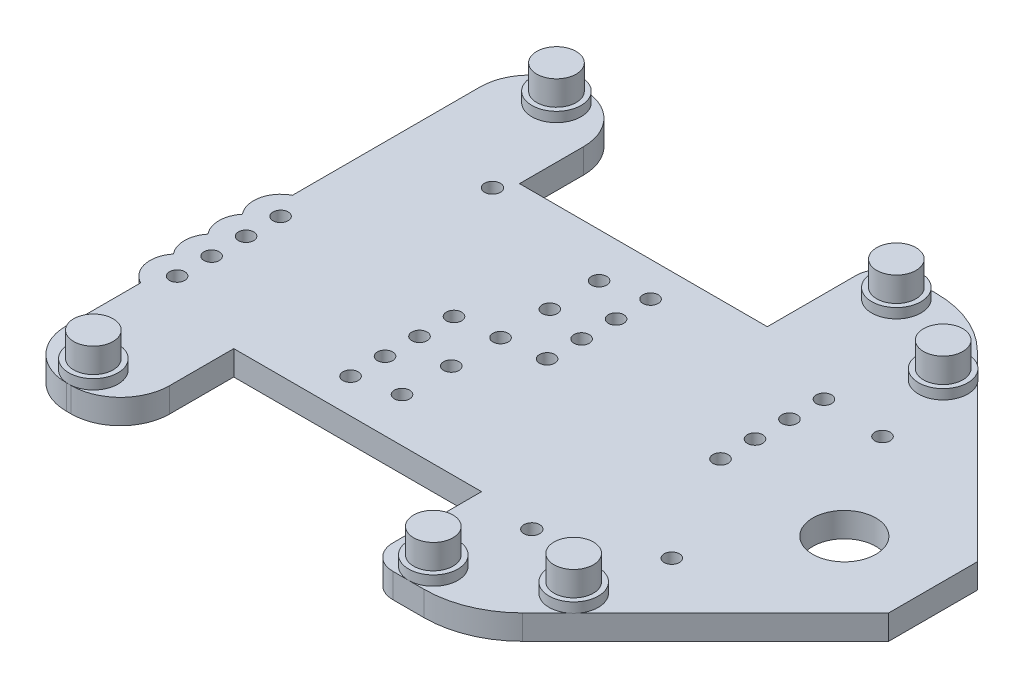
SolidWorks part; units mm, degrees
ref_plane "Front Plane" through (0, 0, 0) normal (0, 0, 1) x (1, 0, 0)
ref_plane "Top Plane" through (0, 0, 0) normal (0, 1, 0) x (1, 0, 0)
ref_plane "Right Plane" through (0, 0, 0) normal (1, 0, 0) x (0, 0, -1)
sketch "Sketch1" plane through (0, 0, 0) normal (0, 1, 0) x (1, 0, 0)
  line L0 (28.5751, 48.8215) -> (28.5751, 67.8215)
  line L3 (-18.8873, 18.9968) -> (28.5751, 48.8215) construction
  line L4 (-18.8873, 20.6462) -> (28.5751, -9.1785) construction
  line L5 (28.5751, -9.1785) -> (28.5751, -28.1785)
  line L6 (28.5751, 48.8215) -> (28.5751, -9.1785) construction
  line L11 (28.5751, 48.8215) -> (26.2701, 48.8215)
  line L17 (-63.7249, 19.8215) -> (-60.0406, 19.8215) construction
  line L19 (-63.7249, -32.1785) -> (-63.7249, -7.0775)
  line L23 (-42.7249, -9.1785) -> (12.2701, -9.1785)
  line L24 (-42.7249, 48.8215) -> (-42.7249, 71.8215)
  line L25 (31.2025, 67.8215) -> (70.2134, 28.8107)
  line L27 (28.5751, -28.1785) -> (31.2025, -28.1785)
  line L28 (25.2701, -10.6735) -> (25.2701, -10.1785)
  line L29 (28.5751, 67.8215) -> (31.2025, 67.8215)
  line L30 (13.2701, -10.6735) -> (13.2701, -10.1785)
  line L31 (26.2701, -9.1785) -> (28.5751, -9.1785)
  line L32 (19.2701, -10.6735) -> (24.1031, -10.6735) construction
  line L33 (13.2701, 50.3165) -> (13.2701, 49.8215)
  line L34 (25.2701, 50.3165) -> (25.2701, 49.8215)
  line L35 (12.2701, 48.8215) -> (-42.7249, 48.8215)
  line L36 (-55.8166, 19.8215) -> (68.9336, 19.8215) construction
  line L37 (-63.7249, 23.7205) -> (-63.7249, 71.8215)
  line L38 (70.2134, 28.8107) -> (70.2134, 10.8324)
  line L39 (70.2134, 10.8324) -> (31.2025, -28.1785)
  line L43 (-42.7249, -9.1785) -> (-42.7249, -32.1785)
  line L46 (-63.7249, -32.1785) -> (-42.7249, -32.1785)
  line L49 (-63.7249, 71.8215) -> (-42.7249, 71.8215)
  circle A0 centre (26.0751, 20.8215) radius 1.55
  circle A1 centre (-9.1249, 20.8215) radius 1.55
  circle A2 centre (-9.1249, 27.8215) radius 1.55
  circle A3 centre (26.0751, 27.8215) radius 1.55
  circle A4 centre (-9.1249, 34.8215) radius 1.55
  circle A5 centre (26.0751, 34.8215) radius 1.55
  circle A6 centre (-9.1249, 41.8215) radius 1.55
  circle A7 centre (26.0751, 41.8215) radius 1.55
  circle A8 centre (-26.0249, -2.1785) radius 1.55
  circle A9 centre (-61.2249, -2.1785) radius 1.55
  circle A10 centre (-26.0249, 4.8215) radius 1.55
  circle A11 centre (-61.2249, 4.8215) radius 1.55
  circle A12 centre (-26.0249, 11.8215) radius 1.55
  circle A13 centre (-61.2249, 11.8215) radius 1.55
  circle A14 centre (-26.0249, 18.8215) radius 1.55
  circle A15 centre (-61.2249, 18.8215) radius 1.55
  circle A16 centre (-17.5749, 39.8215) radius 1.55
  circle A17 centre (-17.5749, 29.8215) radius 1.55
  circle A18 centre (-17.5749, 19.8215) radius 1.55
  circle A19 centre (-17.5749, 9.8215) radius 1.55
  circle A20 centre (-17.5749, -0.1785) radius 1.55
  circle A26 centre (52.2134, 19.8215) radius 6.4
  arc A27 (13.2701, -10.6735) -> (25.2701, -10.6735) centre (19.2701, -10.6735) ccw
  arc A28 (25.2701, -10.1785) -> (26.2701, -9.1785) centre (26.2701, -10.1785) cw
  arc A29 (13.2701, -10.1785) -> (12.2701, -9.1785) centre (12.2701, -10.1785) ccw
  circle A30 centre (19.2701, -10.6735) radius 1.605
  circle A31 centre (-44.7399, 45.3465) radius 1.605
  arc A32 (13.2701, 49.8215) -> (12.2701, 48.8215) centre (12.2701, 49.8215) cw
  arc A33 (13.2701, 50.3165) -> (25.2701, 50.3165) centre (19.2701, 50.3165) cw
  arc A34 (25.2701, 49.8215) -> (26.2701, 48.8215) centre (26.2701, 49.8215) ccw
  arc A36 (-65.4675, 15.3215) -> (-65.4675, 8.3215) centre (-61.2249, 11.8215) ccw
  arc A39 (-63.7249, 23.7205) -> (-65.4675, 15.3215) centre (-61.2249, 18.8215) ccw
  arc A41 (-65.4675, 8.3215) -> (-65.4675, 1.3215) centre (-61.2249, 4.8215) ccw
  arc A43 (-65.4675, 1.3215) -> (-63.7249, -7.0775) centre (-61.2249, -2.1785) ccw
  circle A46 centre (38.5751, 41.2063) radius 1.55
  circle A47 centre (38.5751, -1.5633) radius 1.55
  point P0 (-17.5749, 19.8215)
  point P58 (25.2701, -9.1785)
  dimension "D1" = 58
  dimension "D11" = 3.1
  dimension "D10" = 3.1
  dimension "D15" = 12.8
  dimension "D8" = 12
  dimension "D9" = 1
  dimension "D17" = 37.7
  dimension "D3" = 19
  dimension "D4" = 19
  dimension "D5" = 2.6274
  dimension "D6" = 7
  dimension "D7" = 3.475
  dimension "D13" = 29
  dimension "D14" = 29
  dimension "D16" = 7
  dimension "D18" = 2.5
  dimension "D12" = 5
extrude "Boss-Extrude1" add sketch "Sketch1" along normal blind 5
sketch "Sketch3" plane through (0, 0, 0) normal (0, -1, 0) x (-1, 0, 0)
  circle A1 centre (61.2249, -2.1785) radius 3.05
  circle A2 centre (61.2249, 4.8215) radius 3.05
  circle A3 centre (61.2249, 11.8215) radius 3.05
  circle A4 centre (61.2249, 18.8215) radius 3.05
  circle A6 centre (26.0249, -2.1785) radius 3.05
  circle A7 centre (26.0249, 4.8215) radius 3.05
  circle A8 centre (26.0249, 11.8215) radius 3.05
  circle A9 centre (26.0249, 18.8215) radius 3.05
  circle A10 centre (17.5749, -0.1785) radius 3.05
  circle A11 centre (17.5749, 9.8215) radius 3.05
  circle A12 centre (17.5749, 19.8215) radius 3.05
  circle A13 centre (17.5749, 29.8215) radius 3.05
  circle A14 centre (17.5749, 39.8215) radius 3.05
  circle A15 centre (9.1249, 20.8215) radius 3.05
  circle A16 centre (9.1249, 27.8215) radius 3.05
  circle A17 centre (9.1249, 34.8215) radius 3.05
  circle A18 centre (9.1249, 41.8215) radius 3.05
  circle A21 centre (-26.0751, 20.8215) radius 3.05
  circle A22 centre (-26.0751, 27.8215) radius 3.05
  circle A23 centre (-26.0751, 34.8215) radius 3.05
  circle A24 centre (-26.0751, 41.8215) radius 3.05
  circle A26 centre (-19.2701, -10.6735) radius 3.05
  circle A27 centre (44.7399, 45.3465) radius 3.05
  circle A28 centre (-38.5751, 41.2063) radius 3.05
  circle A29 centre (-38.5751, -1.5633) radius 3.05
extrude "Cut-Extrude1" cut sketch "Sketch3" against normal blind 2
sketch "Sketch6" plane through (0, 0, 0) normal (0, -1, 0) x (-1, 0, 0)
  line L0 (-7.5751, -9.1785) -> (-7.5751, -32.1785) construction
  line L1 (42.7249, -9.1785) -> (-12.2701, -9.1785) construction
  line L2 (-28.5751, -9.1785) -> (-28.5751, -28.1785) construction
  line L3 (-7.5751, -9.1785) -> (-7.5751, -32.1785)
  line L5 (-31.2025, -28.1785) -> (-28.5751, -28.1785)
  line L6 (-28.5751, -28.1785) -> (-28.5751, -9.1785)
  line L7 (-28.5751, -9.1785) -> (-26.2526, -9.1785)
  line L8 (-7.5751, -9.1785) -> (-12.2876, -9.1785)
  line L9 (-70.2134, 19.8215) -> (-38.7405, 19.8215) construction
  line L10 (-70.2134, 10.8324) -> (-70.2134, 28.8107) construction
  line L11 (-7.5751, 48.8215) -> (-7.5751, 71.8215) construction
  line L12 (-7.5751, 48.8215) -> (-12.2876, 48.8215)
  line L13 (-28.5751, 48.8215) -> (-26.2526, 48.8215)
  line L14 (-28.5751, 67.8215) -> (-28.5751, 48.8215)
  line L15 (-31.2025, 67.8215) -> (-28.5751, 67.8215)
  line L17 (-7.5751, 48.8215) -> (-7.5751, 71.8215)
  line L18 (-7.5751, 71.8215) -> (-27.2025, 71.8215)
  line L20 (-7.5751, -32.1785) -> (-27.2025, -32.1785)
  line L22 (-31.2025, -28.1785) -> (-27.2025, -32.1785)
  line L23 (-31.2025, 67.8215) -> (-27.2025, 71.8215)
  arc A0 (-26.2526, -9.1785) -> (-25.2551, -10.2492) centre (-26.2526, -10.1785) cw
  arc A1 (-12.2876, 48.8215) -> (-13.2851, 49.8922) centre (-12.2876, 49.8215) cw
  arc A2 (-25.2551, 49.8922) -> (-13.2851, 49.8922) centre (-19.2701, 50.3165) cw
  arc A3 (-25.2551, -10.2492) -> (-13.2851, -10.2492) centre (-19.2701, -10.6735) ccw
  arc A4 (-12.2876, -9.1785) -> (-13.2851, -10.2492) centre (-12.2876, -10.1785) ccw
  arc A5 (-26.2526, 48.8215) -> (-25.2551, 49.8922) centre (-26.2526, 49.8215) ccw
  dimension "D3" = 1
  dimension "D1" = 23
  dimension "D2" = 21
extrude "Boss-Extrude3" add sketch "Sketch6" against normal blind 5
sketch "Sketch7" plane through (0, 5, 0) normal (0, 1, 0) x (1, 0, 0)
  line L0 (-42.7249, 48.8215) -> (-42.7249, 71.8215) construction
  line L1 (7.5751, 48.8215) -> (-42.7249, 48.8215) construction
  line L2 (70.2134, 19.8215) -> (5.5967, 19.8215) construction
  line L3 (70.2134, 10.8324) -> (70.2134, 28.8107) construction
  circle A0 centre (-53.2249, 66.8215) radius 5
  circle A1 centre (-53.2249, -27.1785) radius 5
  circle A2 centre (15.7751, 66.8215) radius 5
  circle A3 centre (15.7751, -27.1785) radius 5
  circle A4 centre (34.7751, 57.3215) radius 5
  circle A5 centre (34.7751, -17.6785) radius 5
  point P4 (-42.7249, 60.3215)
  dimension "D1" = 10.5
  dimension "D2" = 18
  dimension "D3" = 10
  dimension "D7" = 69
  dimension "D5" = 19
  dimension "D6" = 9.5
  dimension "D4" = 2
extrude "Boss-Extrude4" add sketch "Sketch7" along normal blind 2
sketch "Sketch8" plane through (0, 7, 0) normal (0, 1, 0) x (1, 0, 0)
  line L0 (70.2134, 19.8215) -> (1.4959, 19.8215) construction
  line L1 (70.2134, 10.8324) -> (70.2134, 28.8107) construction
  circle A0 centre (-53.2249, 66.8215) radius 4
  circle A1 centre (-53.2249, -27.1785) radius 4
  circle A2 centre (15.7751, 66.8215) radius 4
  circle A3 centre (15.7751, -27.1785) radius 4
  circle A4 centre (34.7751, 57.3215) radius 4
  circle A5 centre (34.7751, -17.6785) radius 4
  dimension "D2" = 8
  dimension "D3" = 8
  dimension "D4" = 8
  dimension "D6" = 19
  dimension "D5" = 69
  dimension "D7" = 9.5
  dimension "D8" = 19
  dimension "D9" = 9.5
  dimension "D1" = 2
extrude "Boss-Extrude5" add sketch "Sketch8" along normal blind 5
fillet "Fillet1" radius 10 4 edges at (-42.7249, 2.5, -71.8215) (-63.7249, 2.5, -71.8215) (-42.7249, 2.5, 32.1785) (-63.7249, 2.5, 32.1785)
fillet "Fillet2" radius 5 2 edges at (7.5751, 2.5, 32.1785) (7.5751, 2.5, -71.8215)
fillet "Fillet3" radius 20 2 edges at (27.2025, 2.5, -71.8215) (27.2025, 2.5, 32.1785)
